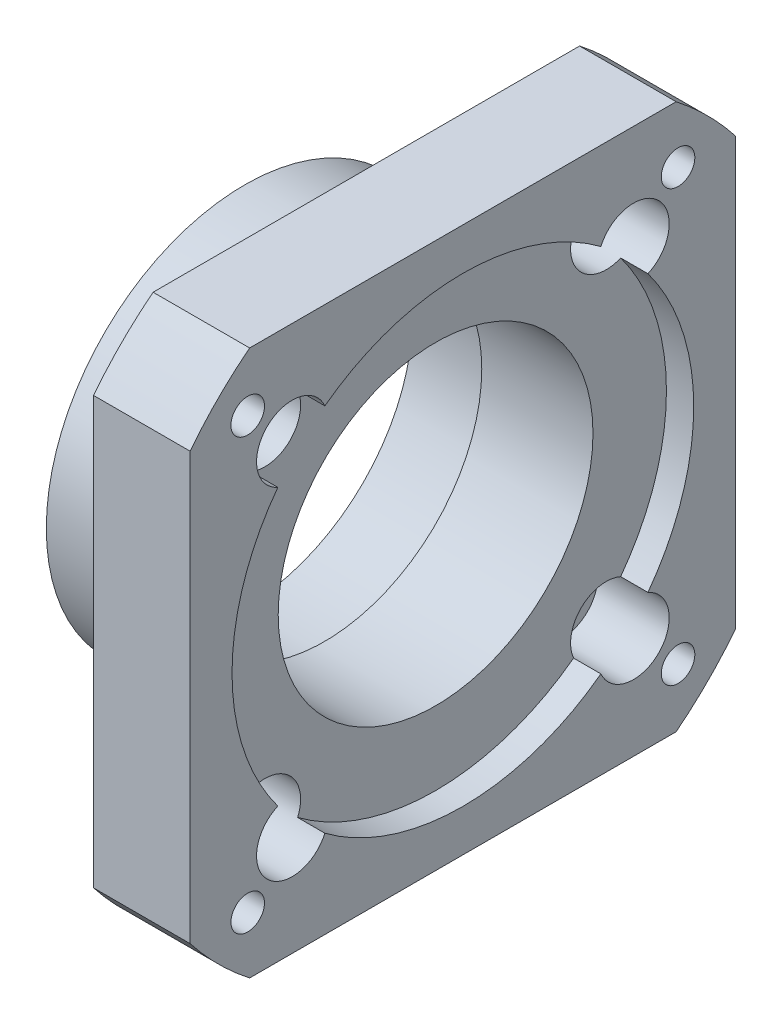
SolidWorks part; units mm, degrees
ref_plane "前视基准面" through (0, 0, 0) normal (0, 0, 1) x (1, 0, 0)
ref_plane "上视基准面" through (0, 0, 0) normal (0, 1, 0) x (1, 0, 0)
ref_plane "右视基准面" through (0, 0, 0) normal (1, 0, 0) x (0, 0, -1)
other "Configuration Table"
sketch "草图2" plane through (0, 0, 0) normal (0, 0, 1) x (1, 0, 0)
  line L0 (0, 37.5) -> (0, 55)
  line L1 (0, 55) -> (6.5, 55)
  line L2 (6.5, 55) -> (6.5, 82.5)
  line L3 (6.5, 82.5) -> (-16.5, 82.5)
  line L4 (-16.5, 82.5) -> (-16.5, 47.25)
  line L5 (-16.5, 47.25) -> (-45.5, 47.25)
  line L6 (-45.5, 47.25) -> (-45.5, 40)
  line L7 (-45.5, 40) -> (-26.5, 40)
  line L8 (-26.5, 40) -> (-26.5, 37.5)
  line L9 (-26.5, 37.5) -> (0, 37.5)
  line L10 (0, 0) -> (45.2214, 0) construction
  point P13 (-36, 40)
  dimension "D1" = 6.5
  dimension "D2" = 23
  dimension "D3" = 110
  dimension "D4" = 75
  dimension "D5" = 80
  dimension "D6" = 19
  dimension "D7" = 29
  dimension "D8" = 94.5
  dimension "D9" = 165
revolve "旋转1" add sketch "草图2" angle 360 about L10
sketch "草图3" plane through (-16.5, 0, 0) normal (-1, 0, 0) x (0, 0, 1)
  line L1 (-65, 65) -> (65, 65)
  line L2 (-65, 65) -> (-65, -65)
  line L3 (-65, -65) -> (65, -65)
  line L4 (65, 65) -> (65, -65)
  line L5 (-65, 65) -> (65, -65) construction
  line L6 (-65, -65) -> (65, 65) construction
  point P0 (0, 0)
  dimension "D1" = 130
extrude "切除-拉伸1" cut sketch "草图3" against normal through all flip side to cut
sketch "草图4" plane through (-45.5, 0, 0) normal (-1, 0, 0) x (0, 0, 1)
  line L0 (0, 0) -> (0, 65) construction
  line L1 (-50.806, 65) -> (50.806, 65) construction
  line L2 (-51.2652, 51.2652) -> (0, 0) construction
  circle A0 centre (-51.2652, 51.2652) radius 4
  circle A1 centre (0, 0) radius 72.5 construction
  circle A2 centre (51.2652, 51.2652) radius 4
  circle A3 centre (51.2652, -51.2652) radius 4
  circle A4 centre (-51.2652, -51.2652) radius 4
  point P8 (47.1069, 44.5769)
  point P9 (0, 0)
  point P17 (0, 0)
  dimension "D1" = 8
  dimension "D2" = 145
  dimension "D3" = 45
  dimension "D4" = 4
extrude "切除-拉伸2" cut sketch "草图4" against normal through all
sketch "草图5" plane through (6.5, 0, 0) normal (-1, 0, 0) x (0, 0, 1)
  circle A0 centre (0, 0) radius 57.5 construction
  dimension "D1" = 115
hole_wizard "M6 六角头螺栓的柱形沉头孔1" positions "草图6" profile "草图7" counterbore size "M6" standard "GB" end condition through all
sketch "草图6" plane through (6.5, 0, 0) normal (1, 0, 0) x (0, 0, -1)
  line L0 (51.2652, 51.2652) -> (0, 0) construction
  circle A0 centre (0, 0) radius 57.5 construction
  point P0 (40.6586, 40.6586)
sketch "草图7" plane through (6.5, 40.6586, -40.6586) normal (0, 1, 0) x (0, 0, -1)
  line L0 (0, 0) -> (0, 52)
  line L1 (0, 52) -> (5.5, 52)
  line L3 (5.5, 52) -> (5.5, 17)
  line L4 (5.5, 17) -> (8.5, 17)
  line L5 (8.5, 17) -> (8.5, 0)
  line L7 (8.5, 0) -> (0, 0)
  line L11 (0, -6.35) -> (0, 107.95) construction
  dimension "通孔孔直径" = 11
  dimension "通孔孔深度" = 52
  dimension "柱形沉头孔直径" = 17
  dimension "柱形沉头孔深度" = 17
pattern_circular "阵列(圆周)1" count 4 over 360 about axis through (0, 0, 0) along (1, 0, 0) of "M6 六角头螺栓的柱形沉头孔1"
